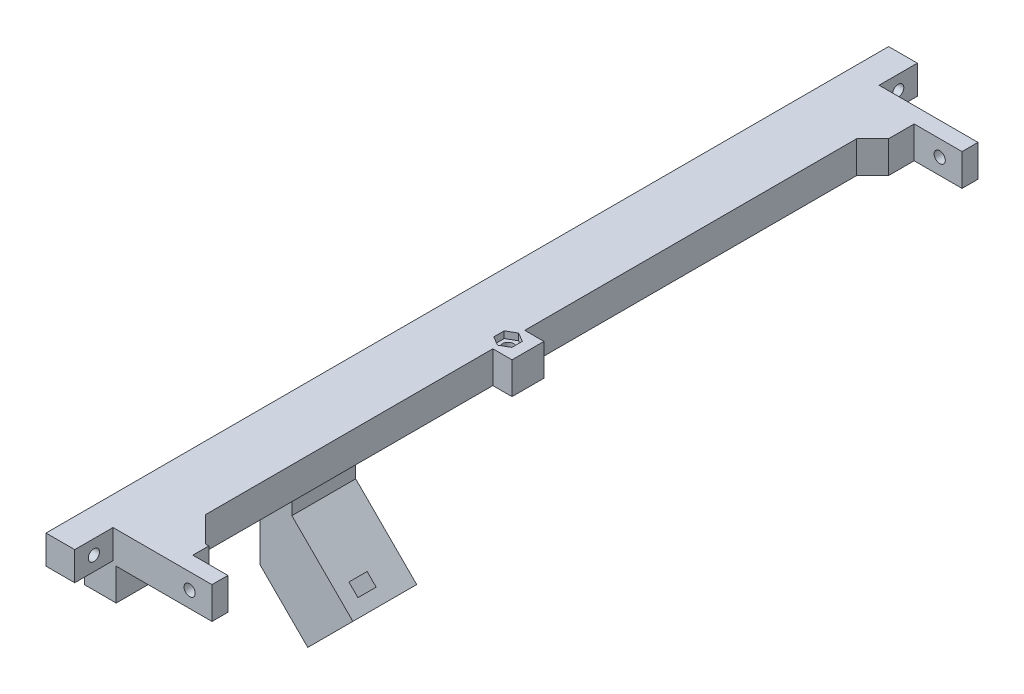
SolidWorks part; units mm, degrees
ref_plane "Front Plane" through (0, 0, 0) normal (0, 0, 1) x (1, 0, 0)
ref_plane "Top Plane" through (0, 0, 0) normal (0, 1, 0) x (1, 0, 0)
ref_plane "Right Plane" through (0, 0, 0) normal (1, 0, 0) x (0, 0, -1)
sketch "Sketch1" plane through (0, 0, 0) normal (0, 0, 1) x (1, 0, 0)
  line L0 (-10, 0) -> (0, 0)
  line L1 (0, 0) -> (0, 10)
  line L2 (0, 10) -> (10, 10)
  line L3 (10, 10) -> (10, 20)
  line L4 (10, 20) -> (-10, 20)
  line L5 (-10, 20) -> (-10, 0)
  dimension "D1" = 10
  dimension "D2" = 20
extrude "Boss-Extrude1" add sketch "Sketch1" along normal blind 240
sketch "Sketch4" plane through (0, 20, 0) normal (0, 1, 0) x (1, 0, 0)
  line L0 (10, 0) -> (30, 0)
  line L1 (30, 0) -> (30, -10)
  line L3 (10, -240) -> (10, 0) construction
  line L8 (10, -18) -> (10, 0)
  line L9 (30, -10) -> (18, -10)
  line L10 (18, -10) -> (10, -18)
  dimension "D1" = 45
  dimension "D2" = 12
  dimension "D3" = 10
  dimension "D4" = 20
extrude "Boss-Extrude3" add sketch "Sketch4" against normal up to surface (10 mm away) up to face at (5, 10, 120)
sketch "Sketch5" plane through (0, 0, 0) normal (0, 0, -1) x (-1, 0, 0)
  line L1 (-30, 10) -> (-30, 20) construction
  circle A0 centre (-23, 15) radius 1.75
  point P4 (-30, 15)
  dimension "D1" = 3.5
  dimension "D2" = 7
extrude "Cut-Extrude1" cut sketch "Sketch5" against normal through all
sketch "Sketch6" plane through (30, 0, 0) normal (1, 0, 0) x (0, 0, -1)
  line L6 (0, 10) -> (0, 20) construction
  line L7 (-12, 21) -> (-5, 21)
  line L8 (-12, 21) -> (-12, 9)
  line L9 (-12, 9) -> (-5, 9)
  line L10 (-5, 21) -> (-5, 9)
  point P6 (0, 15)
  point P7 (-5, 15)
  dimension "D1" = 5
  dimension "D2" = 7
  dimension "D3" = 12
extrude "Cut-Extrude2" cut sketch "Sketch6" against normal blind 11
ref_plane "Plane1" through (0, 0, 120) normal (0, 0, -1) x (-1, 0, 0)
mirror "Mirror1" about plane through (0, 0, 120) normal (0, 0, -1) of "Cut-Extrude1", "Boss-Extrude3", "Cut-Extrude2"
ref_plane "Plane2" through (0, 0, 174.97) normal (0, 0, 1) x (1, 0, 0)
sketch "Sketch7" plane through (0, 0, 174.97) normal (0, 0, 1) x (1, 0, 0)
  line L4 (0, 0) -> (0, -3.8088)
  line L5 (0, -3.8088) -> (19.1202, -22.9289)
  line L7 (-10, 0) -> (-10, -30) construction
  line L8 (-10, -30) -> (12.0491, -30) construction
  line L10 (19.1202, -22.9289) -> (4.978, -37.0711)
  line L11 (4.978, -37.0711) -> (-10, -22.093)
  line L12 (-10, -22.093) -> (-10, 0)
  line L13 (-10, 0) -> (0, 0)
  point P11 (12.0491, -30)
  dimension "D1" = 30
  dimension "D2" = 27.04
  dimension "D3" = 45
  dimension "D4" = 20
extrude "Boss-Extrude5" add sketch "Sketch7" along normal blind 10 and the other way blind 10 contours L11 L12 L13 L4 L5 L10
sketch "Sketch12" plane through (10, 0, 0) normal (1, 0, 0) x (0, 0, -1)
  line L1 (-222, 10) -> (-222, 20) construction
  line L6 (-222, 20) -> (-18, 20) construction
  line L7 (-132, 20) -> (-122, 20)
  line L9 (-132, 20) -> (-132, 10)
  line L10 (-132, 10) -> (-122, 10)
  line L11 (-122, 20) -> (-122, 10)
  line L12 (-222, 20) -> (-18, 20) construction
  line L13 (-222, 10) -> (-18, 10) construction
  dimension "D1" = 10
  dimension "D2" = 90
extrude "Boss-Extrude6" add sketch "Sketch12" along normal blind 6
sketch "Sketch11" plane through (0, 20, 0) normal (0, 1, 0) x (1, 0, 0)
  line L0 (16, -122) -> (16, -132) construction
  line L1 (16, -122) -> (10, -122) construction
  circle A4 centre (9.765, -127) radius 1.75
  dimension "D3" = 5
  dimension "D1" = 3.5
  dimension "D2" = 6.235
extrude "Cut-Extrude6" cut sketch "Sketch11" against normal up to surface (20 mm away) up to face at (-5, 0, 82.485)
sketch "Sketch13" plane through (0, 0, 0) normal (0, 0, -1) x (-1, 0, 0)
  line L1 (10, 20) -> (1, 20)
  line L2 (10, 20) -> (10, 11)
  line L3 (10, 11) -> (1, 11)
  line L4 (1, 20) -> (1, 11)
  dimension "D1" = 9
extrude "Boss-Extrude7" add sketch "Sketch13" along normal blind 12
ref_plane "Plane3" through (0, 0, 120) normal (0, 0, 1) x (1, 0, 0)
mirror "Mirror2" about plane through (0, 0, 120) normal (0, 0, 1) of "Boss-Extrude7"
sketch "Sketch16" plane through (-10, 0, 0) normal (-1, 0, 0) x (0, 0, 1)
  line L0 (-6, 15.5) -> (-12, 15.5) construction
  line L1 (-12, 11) -> (-12, 20) construction
  line L2 (246, 15.5) -> (252, 15.5) construction
  line L3 (252, 11) -> (252, 20) construction
  circle A0 centre (-6, 15.5) radius 1.75
  circle A1 centre (246, 15.5) radius 1.75
  dimension "D1" = 3.5
  dimension "D3" = 6
  dimension "D2" = 6
extrude "Cut-Extrude10" cut sketch "Sketch16" against normal up to surface (9 mm away) up to face at (-1, 15.5, -6)
sketch "Sketch17" plane through (0, 20, 0) normal (0, 1, 0) x (1, 0, 0)
  line L1 (12.615, -128.6454) -> (12.615, -125.3546)
  line L2 (12.615, -125.3546) -> (9.765, -123.7091)
  line L3 (9.765, -123.7091) -> (6.915, -125.3546)
  line L4 (6.915, -125.3546) -> (6.915, -128.6454)
  line L5 (6.915, -128.6454) -> (9.765, -130.2909)
  line L6 (9.765, -130.2909) -> (12.615, -128.6454)
  line L7 (16, -122) -> (16, -132) construction
  circle A0 centre (9.765, -127) radius 2.85 construction
  dimension "D1" = 5.7
extrude "Cut-Extrude11" cut sketch "Sketch17" against normal blind 2.1
sketch "Sketch18" plane through (-10, 0, 0) normal (-1, 0, 0) x (0, 0, 1)
  circle A0 centre (246, 15.5) radius 3
  circle A1 centre (-6, 15.5) radius 3
  dimension "D1" = 6
extrude "Cut-Extrude12" cut sketch "Sketch18" against normal blind 3.1
sketch "Sketch19" plane through (-10, 0, 0) normal (-1, 0, 0) x (0, 0, 1)
  line L1 (164.97, 0) -> (0, 0) construction
  circle A0 centre (100, 5) radius 1.75
  dimension "D1" = 3.5
  dimension "D2" = 100
  dimension "D3" = 5
extrude "Cut-Extrude13" cut sketch "Sketch19" against normal up to surface (10 mm away) up to face at (0, 1.5478, 147.485)
sketch "Sketch20" plane through (-10, 0, 0) normal (-1, 0, 0) x (0, 0, 1)
  line L0 (164.97, 0) -> (0, 0) construction
  line L1 (101.6454, 2.15) -> (103.2909, 5)
  line L2 (103.2909, 5) -> (101.6454, 7.85)
  line L3 (101.6454, 7.85) -> (98.3546, 7.85)
  line L4 (98.3546, 7.85) -> (96.7091, 5)
  line L5 (96.7091, 5) -> (98.3546, 2.15)
  line L6 (98.3546, 2.15) -> (101.6454, 2.15)
  circle A0 centre (100, 5) radius 2.85 construction
  circle A1 centre (100, 5) radius 1.75 construction
  circle A2 centre (100, 5) radius 1.75 construction
  dimension "D1" = 5.7
extrude "Cut-Extrude14" cut sketch "Sketch20" against normal blind 2.1
sketch "Sketch21" plane through (21.0245, -21.0245, 0) normal (0.7071, -0.7071, 0) x (0, 0, -1)
  line L0 (-164.97, -2.6932) -> (-164.97, -22.6932) construction
  line L1 (-164.97, -2.6932) -> (-184.97, -2.6932) construction
  circle A0 centre (-177.71, -12.0532) radius 1.75
  dimension "D1" = 3.5
  dimension "D2" = 12.74
  dimension "D3" = 9.36
extrude "Cut-Extrude15" cut sketch "Sketch21" against normal blind 15
sketch "Sketch22" plane through (-16.0465, -16.0465, 0) normal (-0.7071, -0.7071, 0) x (0, 0, 1)
  line L1 (174.86, -21.7332) -> (180.56, -21.7332)
  line L2 (174.86, -21.7332) -> (174.86, -25.7332)
  line L3 (174.86, -25.7332) -> (180.56, -25.7332)
  line L4 (180.56, -21.7332) -> (180.56, -25.7332)
  line L5 (184.97, -29.7332) -> (184.97, -8.5511) construction
  line L6 (164.97, -29.7332) -> (184.97, -29.7332) construction
  point P4 (177.71, -25.7332)
  dimension "D1" = 5.7
  dimension "D2" = 4
  dimension "D3" = 7.26
  dimension "D4" = 4
extrude "Cut-Extrude16" cut sketch "Sketch22" against normal through all
sketch "Sketch23" plane through (0, 20, 0) normal (0, 1, 0) x (1, 0, 0)
  line L0 (19, -5) -> (15, -5)
  line L1 (15, -5) -> (15, -13)
  line L2 (10, -18) -> (18, -10) construction
  line L3 (19, -5) -> (19, -10) construction
  line L4 (18, -10) -> (19, -10) construction
  line L5 (19, -5) -> (19, -10)
  line L6 (10, -18) -> (18, -10)
  line L7 (18, -10) -> (19, -10)
  line M18 (10, -18) -> (18, -10)
  line M19 (18, -10) -> (19, -10)
  line M20 (19, -10) -> (19, -5)
  dimension "D1" = 4
extrude "Cut-Extrude17" cut sketch "Sketch23" against normal blind 10 contours L0 L1 M18 M19 M20
